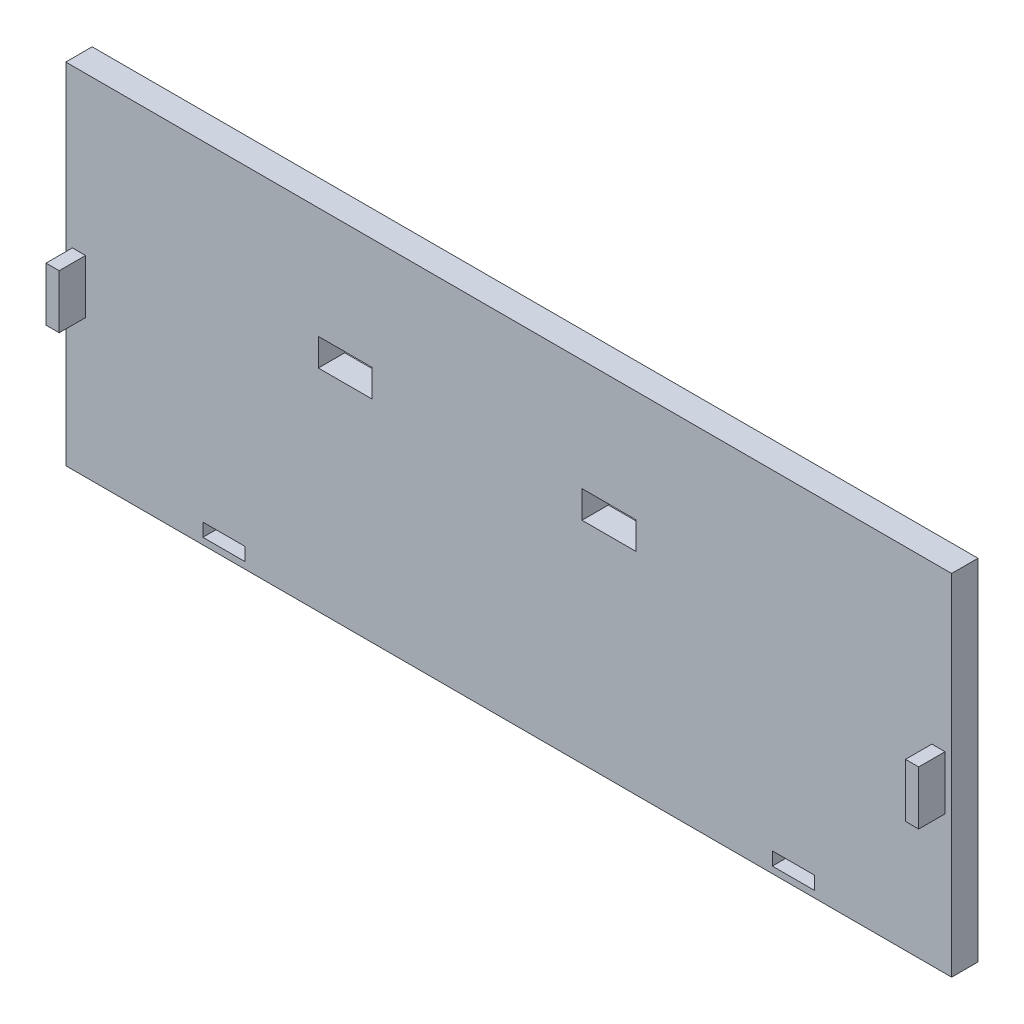
SolidWorks part; units mm, degrees
ref_plane "Alzado" through (0, 0, 0) normal (0, 0, 1) x (1, 0, 0)
ref_plane "Planta" through (0, 0, 0) normal (0, 1, 0) x (1, 0, 0)
ref_plane "Vista lateral" through (0, 0, 0) normal (1, 0, 0) x (0, 0, -1)
sketch "Croquis2" plane through (0, 0, 0) normal (0, 0, 1) x (1, 0, 0)
  line L0 (0, 0) -> (0, 66.31)
  line L1 (0, 66.31) -> (168, 66.31)
  line L2 (168, 66.31) -> (168, 0)
  line L3 (168, 0) -> (0, 0)
  dimension "D1" = 66.31
  dimension "D2" = 168
extrude "Saliente-Extruir1" add sketch "Croquis2" against normal blind 5
sketch "Croquis3" plane through (0, 0, 0) normal (0, 0, 1) x (1, 0, 0)
  line L0 (5, 66.31) -> (5, 0) construction
  line L1 (168, 66.31) -> (0, 66.31) construction
  line L2 (0, 0) -> (168, 0) construction
  line L3 (2.5, 66.31) -> (2.5, 0) construction
  line L6 (1.25, 26.21) -> (3.75, 26.21)
  line L7 (1.25, 26.21) -> (1.25, 36.41)
  line L8 (1.25, 36.41) -> (3.75, 36.41)
  line L9 (3.75, 26.21) -> (3.75, 36.41)
  line L10 (1.25, 26.21) -> (3.75, 36.41) construction
  line L11 (1.25, 36.41) -> (3.75, 26.21) construction
  point P10 (2.5, 31.31)
  dimension "D1" = 5
  dimension "D2" = 10.2
  dimension "D3" = 2.5
  dimension "D4" = 35
extrude "Saliente-Extruir3" add sketch "Croquis3" along normal blind 5
sketch "Croquis5" plane through (0, 0, 0) normal (0, 0, 1) x (1, 0, 0)
  line L3 (0, 0) -> (168, 0) construction
  line L11 (108.1, 40) -> (97.9, 40)
  line L12 (108.1, 40) -> (108.1, 45.2)
  line L13 (108.1, 45.2) -> (97.9, 45.2)
  line L14 (97.9, 40) -> (97.9, 45.2)
  line L15 (168, 0) -> (168, 66.31) construction
  line L17 (58.1, 40) -> (47.9, 40)
  line L18 (58.1, 40) -> (58.1, 45.2)
  line L19 (58.1, 45.2) -> (47.9, 45.2)
  line L20 (47.9, 40) -> (47.9, 45.2)
  dimension "D1" = 59.9
  dimension "D2" = 40
  dimension "D3" = 10.2
  dimension "D4" = 5.2
  dimension "D6" = 50
  dimension "D7" = 10.2
  dimension "D8" = 5.2
extrude "Cortar-Extruir2" cut sketch "Croquis5" against normal through all contours L14 L11 L12 L13 | L18 L17 L20 L19
sketch "Croquis7" plane through (0, 0, 0) normal (0, 0, 1) x (1, 0, 0)
  line L0 (0, 0) -> (0, 5) construction
  line L1 (0, 66.31) -> (0, 0) construction
  line L2 (0, 2.5) -> (168, 2.5) construction
  line L3 (168, 0) -> (168, 66.31) construction
  line L5 (26, 3.75) -> (34, 3.75)
  line L6 (26, 3.75) -> (26, 1.25)
  line L7 (26, 1.25) -> (34, 1.25)
  line L8 (34, 3.75) -> (34, 1.25)
  line L9 (26, 3.75) -> (34, 1.25) construction
  line L10 (26, 1.25) -> (34, 3.75) construction
  line L11 (134, 1.25) -> (142, 1.25)
  line L12 (134, 1.25) -> (134, 3.75)
  line L13 (134, 3.75) -> (142, 3.75)
  line L14 (142, 1.25) -> (142, 3.75)
  point P9 (30, 2.5)
  point P15 (138, 2.5)
  dimension "D1" = 5
  dimension "D2" = 2.5
  dimension "D3" = 8
  dimension "D4" = 30
  dimension "D5" = 30
  dimension "D6" = 8
  dimension "D7" = 2.5
extrude "Cortar-Extruir3" cut sketch "Croquis7" against normal through all
sketch "Sketch1" plane through (0, 0, 0) normal (0, 0, 1) x (1, 0, 0)
  line L0 (168, 66.31) -> (163, 66.31) construction
  line L1 (168, 66.31) -> (0, 66.31) construction
  line L2 (163, 66.31) -> (163, 0) construction
  line L3 (0, 0) -> (168, 0) construction
  line L4 (165.5, 66.31) -> (165.5, 0) construction
  line L6 (164.25, 36.41) -> (166.75, 36.41)
  line L7 (164.25, 36.41) -> (164.25, 26.21)
  line L8 (164.25, 26.21) -> (166.75, 26.21)
  line L9 (166.75, 36.41) -> (166.75, 26.21)
  line L10 (164.25, 36.41) -> (166.75, 26.21) construction
  line L11 (164.25, 26.21) -> (166.75, 36.41) construction
  point P10 (165.5, 31.31)
  dimension "D1" = 5
  dimension "D2" = 35
  dimension "D3" = 10.2
  dimension "D4" = 2.5
extrude "Boss-Extrude1" add sketch "Sketch1" along normal blind 5
